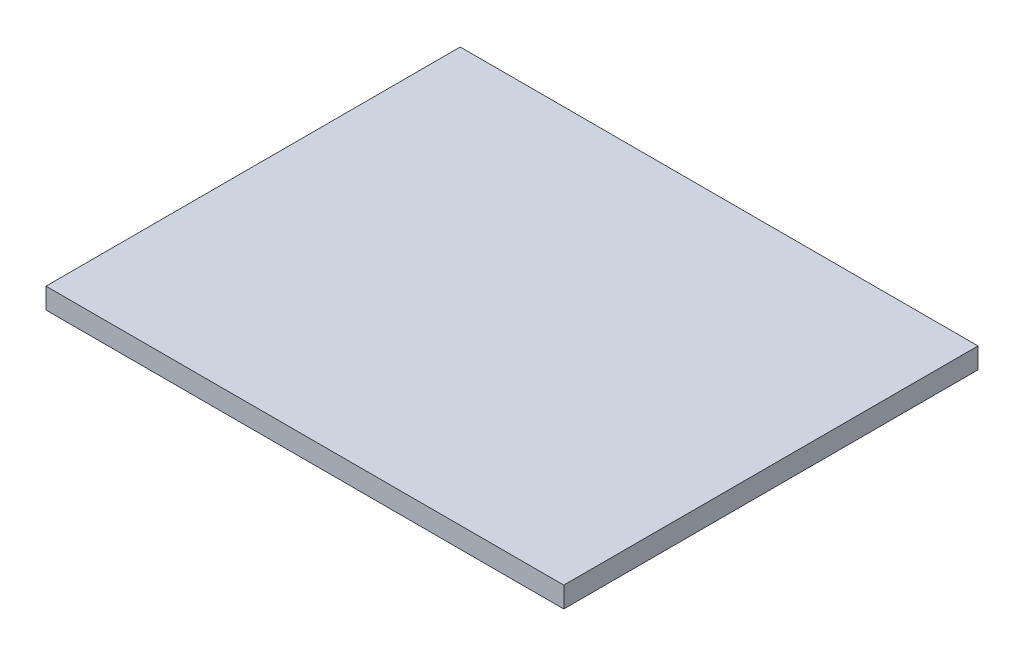
SolidWorks part; units mm, degrees
ref_plane "Спереди" through (0, 0, 0) normal (0, 0, 1) x (1, 0, 0)
ref_plane "Сверху" through (0, 0, 0) normal (0, 1, 0) x (1, 0, 0)
ref_plane "Справа" through (0, 0, 0) normal (1, 0, 0) x (0, 0, -1)
sketch "Эскиз1" plane through (0, 0, 0) normal (0, 1, 0) x (1, 0, 0)
  line L1 (2500, -2000) -> (-2500, -2000)
  line L2 (2500, -2000) -> (2500, 2000)
  line L3 (2500, 2000) -> (-2500, 2000)
  line L4 (-2500, -2000) -> (-2500, 2000)
  line L5 (2500, -2000) -> (-2500, 2000) construction
  line L6 (2500, 2000) -> (-2500, -2000) construction
  point P0 (0, 0)
  dimension "D1" = 5000
  dimension "D2" = 4000
extrude "Бобышка-Вытянуть1" add sketch "Эскиз1" along normal blind 200
